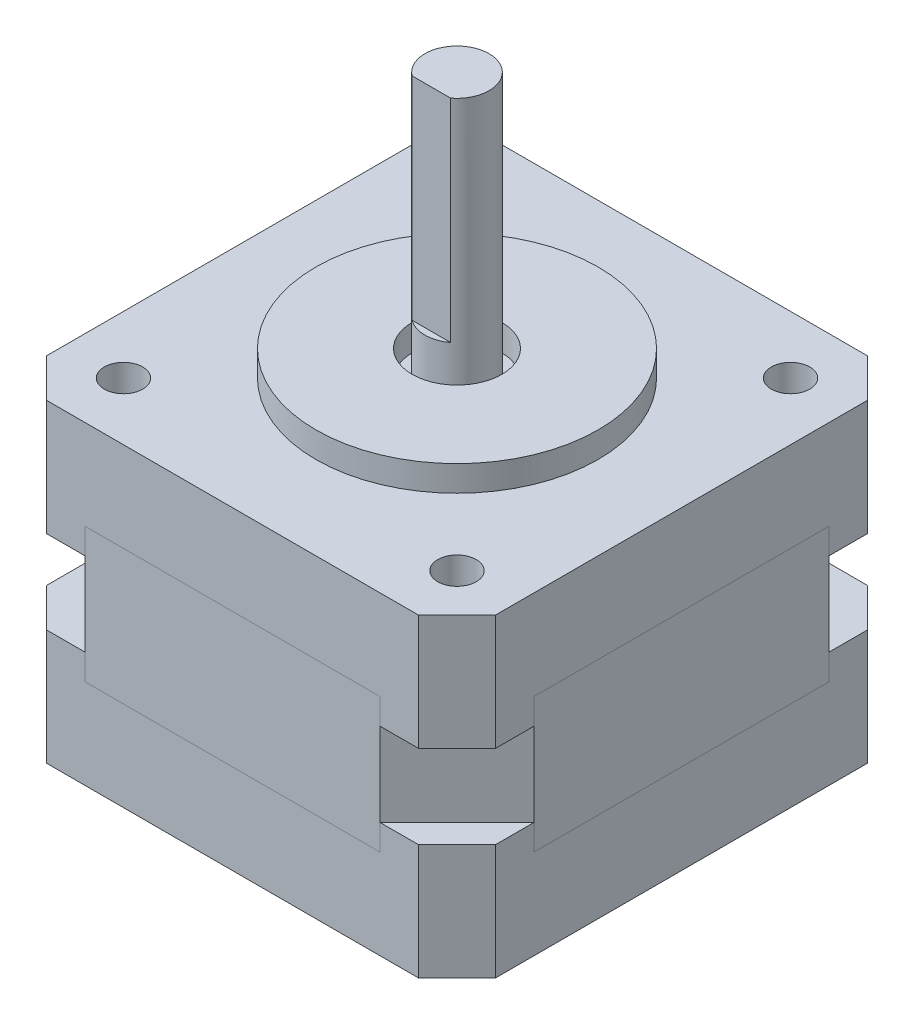
SolidWorks part; units mm, degrees
ref_plane "Front Plane" through (0, 0, 0) normal (0, 0, 1) x (1, 0, 0)
ref_plane "Top Plane" through (0, 0, 0) normal (0, 1, 0) x (1, 0, 0)
ref_plane "Right Plane" through (0, 0, 0) normal (1, 0, 0) x (0, 0, -1)
sketch "Sketch1" plane through (0, 0, 0) normal (0, 1, 0) x (1, 0, 0)
  line L0 (-17.5, 14.5) -> (-14.5, 17.5)
  line L1 (-14.5, -17.5) -> (14.5, -17.5)
  line L2 (-17.5, -14.5) -> (-17.5, 14.5)
  line L3 (-14.5, 17.5) -> (14.5, 17.5)
  line L4 (17.5, -14.5) -> (17.5, 14.5)
  line L5 (-17.5, -17.5) -> (17.5, 17.5) construction
  line L6 (-17.5, 17.5) -> (17.5, -17.5) construction
  line L7 (14.5, 17.5) -> (17.5, 14.5)
  line L8 (14.5, -17.5) -> (17.5, -14.5)
  line L9 (-17.5, -14.5) -> (-14.5, -17.5)
  point P0 (0, 0)
  dimension "D1" = 35
  dimension "D2" = 35
extrude "Boss-Extrude1" add sketch "Sketch1" against normal blind 9
sketch "Sketch9" plane through (0, -9, 0) normal (0, -1, 0) x (1, 0, 0)
  line L18 (0, -17.5) -> (0, 17.5) construction
  line L19 (14.5, -17.5) -> (-14.5, -17.5) construction
  line L20 (-14.5, 17.5) -> (14.5, 17.5) construction
  line L21 (-11.5, -17.5) -> (11.5, -17.5)
  line L22 (11.5, -17.5) -> (17.5, -11.5)
  line L23 (17.5, 14.5) -> (17.5, -14.5) construction
  line L24 (17.5, 0) -> (-17.5, 0) construction
  line L25 (-17.5, -14.5) -> (-17.5, 14.5) construction
  line L26 (17.5, -11.5) -> (17.5, 11.5)
  line L27 (-11.5, -17.5) -> (-17.5, -11.5)
  line L28 (-17.5, -11.5) -> (-17.5, 11.5)
  line L29 (-11.5, 17.5) -> (-17.5, 11.5)
  line L30 (11.5, 17.5) -> (17.5, 11.5)
  line L31 (-11.5, 17.5) -> (11.5, 17.5)
  dimension "D1" = 11.5
  dimension "D2" = 11.5
extrude "Cut-Extrude7" cut sketch "Sketch9" against normal blind 2
sketch "Sketch10" plane through (0, -7, 0) normal (0, -1, 0) x (1, 0, 0)
  line L0 (11.5, -17.5) -> (-11.5, -17.5)
  line L1 (-11.5, -17.5) -> (-17.5, -11.5)
  line L2 (-17.5, -11.5) -> (-17.5, 11.5)
  line L3 (-17.5, 11.5) -> (-11.5, 17.5)
  line L4 (-11.5, 17.5) -> (11.5, 17.5)
  line L5 (11.5, 17.5) -> (17.5, 11.5)
  line L6 (17.5, 11.5) -> (17.5, -11.5)
  line L7 (17.5, -11.5) -> (11.5, -17.5)
extrude "Boss-Extrude2" add sketch "Sketch10" along normal blind 10.5 separate body
ref_plane "Plane1" through (0, -12.25, 0) normal (0, 1, 0) x (1, 0, 0)
mirror "Mirror3" about plane through (0, -12.25, 0) normal (0, 1, 0) of bodies 112
sketch "Sketch11" plane through (0, 0, 0) normal (0, 1, 0) x (1, 0, 0)
  circle A0 centre (0, 0) radius 11
  dimension "D1" = 22
extrude "Boss-Extrude3" add sketch "Sketch11" along normal blind 2
sketch "Sketch12" plane through (0, -7, 0) normal (0, 1, 0) x (1, 0, 0)
  circle A0 centre (0, 0) radius 2.5
  dimension "D1" = 5
extrude "Cut-Extrude8" cut sketch "Sketch12" against normal up to next (10.5 mm away)
sketch "Sketch13" plane through (0, 2, 0) normal (0, 1, 0) x (1, 0, 0)
  circle A0 centre (0, 0) radius 3.5
  dimension "D1" = 7
extrude "Cut-Extrude9" cut sketch "Sketch13" against normal through all
sketch "Sketch14" plane through (0, 0, 0) normal (0, 1, 0) x (1, 0, 0)
  circle A0 centre (0, 0) radius 2.5
  dimension "D1" = 5
extrude "Boss-Extrude4" add sketch "Sketch14" along normal blind 20.65
sketch "Sketch17" plane through (0, -24.5, 0) normal (0, -1, 0) x (1, 0, 0)
  circle A0 centre (0, 0) radius 2.5
  dimension "D1" = 5
extrude "Boss-Extrude5" add sketch "Sketch17" against normal up to surface (22.5 mm away) from offset 2 up to face at (0, 0, 2.5) offset against normal yes
sketch "Sketch15" plane through (0, 20.65, 0) normal (0, 1, 0) x (1, 0, 0)
  line L0 (0, 2.5) -> (0, -2) construction
  line L1 (0, -2) -> (-1.5, -2)
  line L2 (0, -2) -> (1.5, -2)
  line L3 (0, -2) -> (0, -2.5) construction
  circle A0 centre (0, 0) radius 2.5 construction
  arc A2 (-1.5, -2) -> (1.5, -2) centre (0, 0) ccw
  circle A3 centre (0, 0) radius 2.5 construction
  dimension "D2" = 2.5
  dimension "D1" = 4.5
extrude "Cut-Extrude10" cut sketch "Sketch15" against normal blind 16.5
sketch "Sketch18" plane through (0, 0, 0) normal (0, 1, 0) x (1, 0, 0)
  line L0 (0, 17.5) -> (0, -17.5) construction
  line L1 (14.5, 17.5) -> (-14.5, 17.5) construction
  line L2 (-14.5, -17.5) -> (14.5, -17.5) construction
  line L3 (-17.5, 0) -> (17.5, 0) construction
  line L4 (-17.5, 14.5) -> (-17.5, -14.5) construction
  line L5 (17.5, -14.5) -> (17.5, 14.5) construction
  circle A0 centre (-13, 13) radius 1.5
  circle A1 centre (13, 13) radius 1.5
  circle A2 centre (13, -13) radius 1.5
  circle A3 centre (-13, -13) radius 1.5
  dimension "D1" = 13
  dimension "D2" = 13
  dimension "D3" = 3
extrude "Cut-Extrude11" cut sketch "Sketch18" against normal blind 4
sketch "Sketch19" plane through (0, 0, 0) normal (0, 1, 0) x (1, 0, 0)
  circle A0 centre (0, 0) radius 3.45
  circle A1 centre (0, 0) radius 2.55
  dimension "D1" = 6.9
  dimension "D2" = 5.1
extrude "Boss-Extrude6" add sketch "Sketch19" against normal blind 1 separate body
